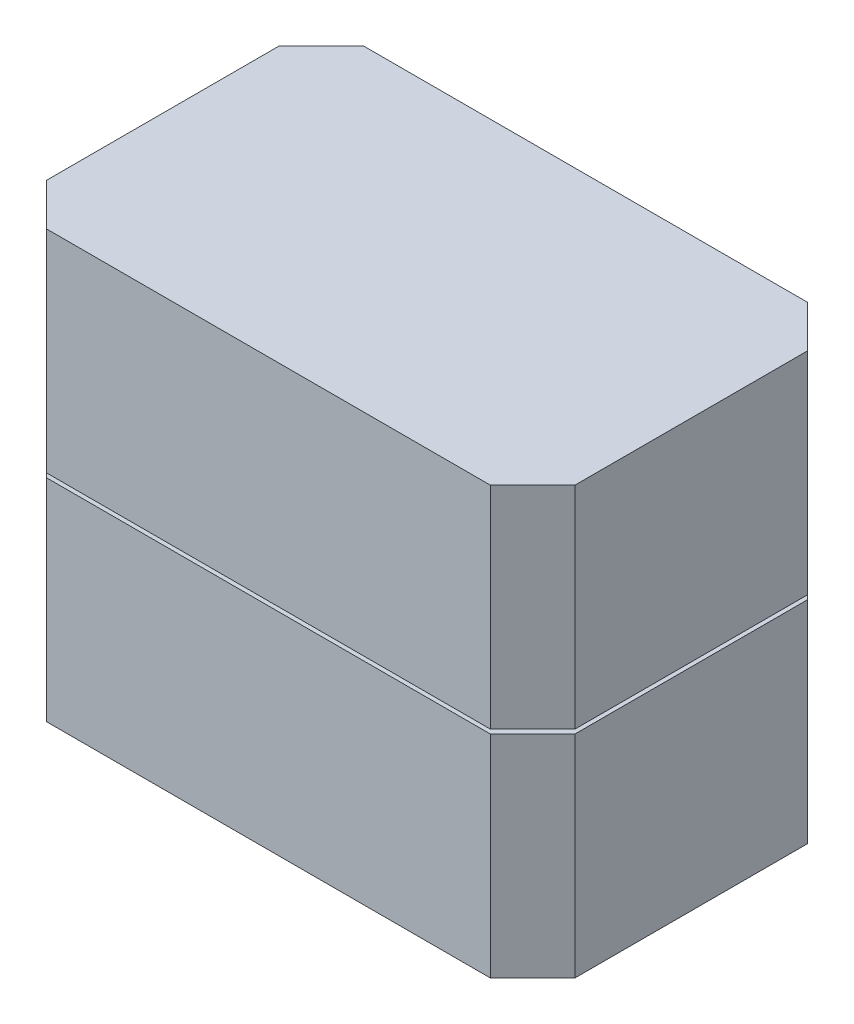
SolidWorks part; units mm, degrees
ref_plane "Front" through (0, 0, 0) normal (0, 0, 1) x (1, 0, 0)
ref_plane "Top" through (0, 0, 0) normal (0, 1, 0) x (1, 0, 0)
ref_plane "Right" through (0, 0, 0) normal (1, 0, 0) x (0, 0, -1)
sketch "Sketch2" plane through (0, 0, 0) normal (0, 1, 0) x (1, 0, 0)
  line L0 (-4.4, -4.95) -> (-2.9, -4.95) construction
  line L1 (-12.5, -7.5) -> (12.5, -7.5)
  line L2 (-12.5, -7.5) -> (-12.5, 7.5)
  line L3 (-12.5, 7.5) -> (12.5, 7.5)
  line L4 (12.5, -7.5) -> (12.5, 7.5)
  line L5 (-12.5, -7.5) -> (12.5, 7.5) construction
  line L6 (-12.5, 7.5) -> (12.5, -7.5) construction
  line L7 (-2.9, -4.95) -> (-1.4, -4.95) construction
  line L8 (-1.4, -4.95) -> (0.1, -4.95) construction
  line L9 (0.1, -4.95) -> (1.6, -4.95) construction
  line L10 (10, 5.75) -> (10, -5.75) construction
  circle A0 centre (1.6, -4.95) radius 0.5
  circle A1 centre (0.1, -4.95) radius 0.5
  circle A2 centre (-1.4, -4.95) radius 0.5
  circle A3 centre (-2.9, -4.95) radius 0.5
  circle A4 centre (-4.4, -4.95) radius 0.5
  circle A5 centre (10, -5.75) radius 0.5
  circle A6 centre (10, 5.75) radius 0.5
  point P0 (0, 0)
  point P13 (10, 0)
  dimension "D8" = 1
  dimension "D1" = 11.5
  dimension "D2" = 22.5
  dimension "D3" = 1.5
  dimension "D4" = 4.95
  dimension "D5" = 8.1
  dimension "D6" = 15
  dimension "D7" = 25
extrude "Boss-Extrude1" add sketch "Sketch2" along normal blind 5
sketch "Sketch3" plane through (0, 5, 0) normal (0, 1, 0) x (1, 0, 0)
  line L0 (11.3, -6.3) -> (11.3, 6.3)
  line L1 (11.3, 6.3) -> (-11.3, 6.3)
  line L2 (-11.3, 6.3) -> (-11.3, -6.3)
  line L3 (-11.3, -6.3) -> (11.3, -6.3)
  line L4 (12.5, -7.5) -> (12.5, 7.5)
  line L5 (12.5, 7.5) -> (-12.5, 7.5)
  line L6 (-12.5, 7.5) -> (-12.5, -7.5)
  line L7 (-12.5, -7.5) -> (12.5, -7.5)
  line L8 (12.5, -7.5) -> (12.5, 7.5)
  line L9 (12.5, 7.5) -> (-12.5, 7.5)
  line L10 (-12.5, 7.5) -> (-12.5, -7.5)
  line L11 (-12.5, -7.5) -> (12.5, -7.5)
  dimension "D1" = 0
  dimension "D2" = 1.2
extrude "Boss-Extrude2" add sketch "Sketch3" along normal blind 5
chamfer "Chamfer1" distance 1 angle 45 4 edges at (-11.3, 7.5, -6.3) (-11.3, 7.5, 6.3) (11.3, 7.5, 6.3) (11.3, 7.5, -6.3)
chamfer "Chamfer2" distance 2 angle 45 4 edges at (12.5, 5, -7.5) (12.5, 5, 7.5) (-12.5, 5, -7.5) (-12.5, 5, 7.5)
sketch "Sketch4" plane through (0, 5, 0) normal (0, 1, 0) x (1, 0, 0)
  line L0 (10.3, 6.3) -> (-10.3, 6.3) construction
  line L1 (-11.1, -4) -> (11.1, -4)
  line L2 (-11.1, -4) -> (-11.1, 4)
  line L3 (-11.1, 4) -> (11.1, 4)
  line L4 (11.1, -4) -> (11.1, 4)
  line L5 (-11.1, -4) -> (11.1, 4) construction
  line L6 (-11.1, 4) -> (11.1, -4) construction
  line L7 (-5.5, -4) -> (-9.5, -4)
  line L8 (-5.5, -4) -> (-5.5, -6.1)
  line L9 (-5.5, -6.1) -> (-9.5, -6.1)
  line L10 (-9.5, -4) -> (-9.5, -6.1)
  line L11 (3, -4) -> (9, -4)
  line L12 (3, -4) -> (3, -6.1)
  line L13 (3, -6.1) -> (9, -6.1)
  line L14 (9, -4) -> (9, -6.1)
  line L15 (9, 4) -> (-9, 4)
  line L16 (9, 4) -> (9, 6.1)
  line L17 (9, 6.1) -> (-9, 6.1)
  line L18 (-9, 4) -> (-9, 6.1)
  line L19 (11.3, -5.3) -> (11.3, 5.3) construction
  line L20 (-10.3, -6.3) -> (10.3, -6.3) construction
  point P0 (0, 0)
  point P24 (0, 6.1)
  dimension "D1" = 0.2
  dimension "D2" = 0.2
  dimension "D3" = 0.2
  dimension "D4" = 8
  dimension "D5" = 18
  dimension "D6" = 6
  dimension "D7" = 4
  dimension "D8" = 5.5
  dimension "D9" = 3
extrude "Boss-Extrude3" add sketch "Sketch4" along normal offset from surface (4 mm away) 0.2 from offset 1.2 separate body contours L18 L3 L16 L17 | L1 L4 L3 L2 | L1 L10 L9 L8 | L14 L1 L12 L13 up to face at (0, 10, 0) offset beyond the face yes
sketch "Sketch5" plane through (0, 10.2, 0) normal (0, 1, 0) x (1, 0, 0)
  line L16 (9, 4) -> (9, 6.3)
  line L17 (10.3, 6.3) -> (-10.3, 6.3) construction
  line L18 (9, 6.3) -> (10.3, 6.3)
  line L19 (10.3, 6.3) -> (11.3, 5.3)
  line L20 (11.3, 5.3) -> (11.3, 4)
  line L21 (11.3, 4) -> (9, 4)
  line L22 (9, -4) -> (11.3, -4)
  line L23 (11.3, -5.3) -> (11.3, 5.3) construction
  line L24 (12.5, -5.5) -> (12.5, 5.5)
  line L25 (12.5, 5.5) -> (10.5, 7.5)
  line L26 (10.5, 7.5) -> (-10.5, 7.5)
  line L27 (-10.5, 7.5) -> (-12.5, 5.5)
  line L28 (-12.5, 5.5) -> (-12.5, -5.5)
  line L29 (-12.5, -5.5) -> (-10.5, -7.5)
  line L30 (-10.5, -7.5) -> (10.5, -7.5)
  line L31 (10.5, -7.5) -> (12.5, -5.5)
  line L32 (12.5, -5.5) -> (12.5, 5.5)
  line L33 (12.5, 5.5) -> (10.5, 7.5)
  line L34 (10.5, 7.5) -> (-10.5, 7.5)
  line L35 (-10.5, 7.5) -> (-12.5, 5.5)
  line L36 (-12.5, 5.5) -> (-12.5, -5.5)
  line L37 (-12.5, -5.5) -> (-10.5, -7.5)
  line L38 (-10.5, -7.5) -> (10.5, -7.5)
  line L39 (10.5, -7.5) -> (12.5, -5.5)
  line L40 (11.3, -4) -> (11.3, -5.3)
  line L41 (11.3, -5.3) -> (10.3, -6.3)
  line L42 (10.3, -6.3) -> (9, -6.3)
  line L43 (-10.3, -6.3) -> (10.3, -6.3) construction
  line L44 (9, -6.3) -> (9, -4)
  line L45 (3, -4) -> (3, -6.3)
  line L46 (-10.3, -6.3) -> (10.3, -6.3) construction
  line L47 (3, -6.3) -> (-5.5, -6.3)
  line L48 (-5.5, -6.3) -> (-5.5, -4)
  line L49 (-5.5, -4) -> (3, -4)
  dimension "D1" = 0
extrude "Boss-Extrude4" add sketch "Sketch5" along normal blind 8
sketch "Sketch6" plane through (0, 18.2, 0) normal (0, 1, 0) x (1, 0, 0)
  line L8 (10.5, -7.5) -> (12.5, -5.5)
  line L9 (12.5, -5.5) -> (12.5, 5.5)
  line L10 (12.5, 5.5) -> (10.5, 7.5)
  line L11 (10.5, 7.5) -> (-10.5, 7.5)
  line L12 (-10.5, 7.5) -> (-12.5, 5.5)
  line L13 (-12.5, 5.5) -> (-12.5, -5.5)
  line L14 (-12.5, -5.5) -> (-10.5, -7.5)
  line L15 (-10.5, -7.5) -> (10.5, -7.5)
  line L16 (10.5, -7.5) -> (12.5, -5.5)
  line L17 (12.5, -5.5) -> (12.5, 5.5)
  line L18 (12.5, 5.5) -> (10.5, 7.5)
  line L19 (10.5, 7.5) -> (-10.5, 7.5)
  line L20 (-10.5, 7.5) -> (-12.5, 5.5)
  line L21 (-12.5, 5.5) -> (-12.5, -5.5)
  line L22 (-12.5, -5.5) -> (-10.5, -7.5)
  line L23 (-10.5, -7.5) -> (10.5, -7.5)
  dimension "D1" = 0
extrude "Boss-Extrude5" add sketch "Sketch6" along normal blind 2
